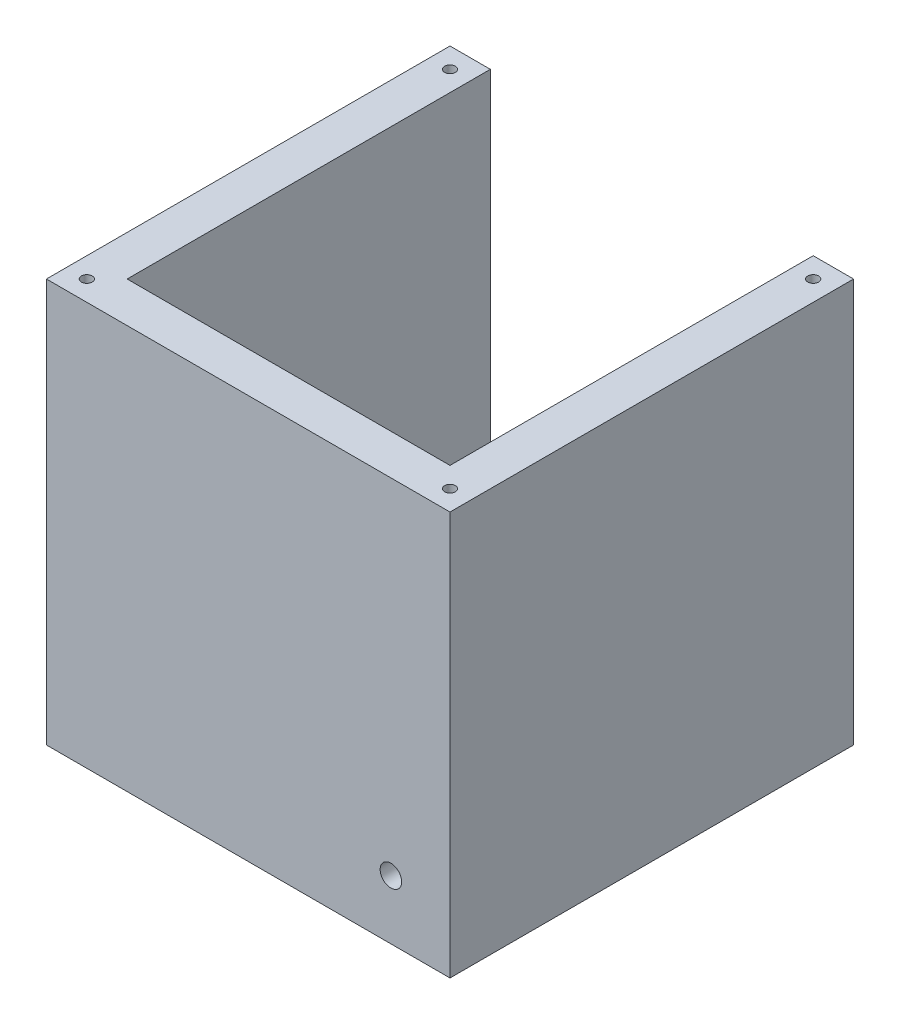
SolidWorks part; units mm, degrees
ref_plane "Alzado" through (0, 0, 0) normal (0, 0, 1) x (1, 0, 0)
ref_plane "Planta" through (0, 0, 0) normal (0, 1, 0) x (1, 0, 0)
ref_plane "Vista lateral" through (0, 0, 0) normal (1, 0, 0) x (0, 0, -1)
sketch "Croquis1" plane through (0, 0, 0) normal (0, 0, 1) x (1, 0, 0)
  line L1 (-75, -75) -> (75, -75)
  line L2 (-75, -75) -> (-75, 75)
  line L3 (-75, 75) -> (75, 75)
  line L4 (75, -75) -> (75, 75)
  line L5 (-75, -75) -> (75, 75) construction
  line L6 (-75, 75) -> (75, -75) construction
  point P0 (0, 0)
extrude "Saliente-Extruir1" add sketch "Croquis1" along normal blind 150
sketch "Croquis2" plane through (0, 0, 0) normal (0, 0, -1) x (-1, 0, 0)
  line L0 (60, 60) -> (60, -60)
  line L1 (60, 60) -> (-60, 60)
  line L2 (60, -60) -> (-60, -60)
  line L3 (-60, 60) -> (-60, -60)
  line L4 (60, 60) -> (-60, -60) construction
  line L5 (60, -60) -> (-60, 60) construction
  line L6 (-60, 60) -> (-60, 75)
  line L7 (-75, 75) -> (75, 75) construction
  line L8 (-60, 75) -> (60, 75)
  line L9 (60, 75) -> (60, 60)
  point P1 (0, 0)
  line M4 (75, 75) -> (-75, 75)
extrude "Cortar-Extruir1" cut sketch "Croquis2" against normal blind 135 contours L9 L6 L1 M4 | L1 L3 L2 L0
sketch "Croquis3" plane through (0, 75, 0) normal (0, 1, 0) x (1, 0, 0)
  line L0 (-60, -135) -> (-75, -150)
  circle A0 centre (-67.5, -142.5) radius 2
  circle A1 centre (67.5, -142.5) radius 2
  circle A2 centre (67.5, -7.5) radius 2
  circle A3 centre (-67.5, -7.5) radius 2
  dimension "D1" = 2
  dimension "D2" = 2
extrude "Cortar-Extruir2" cut sketch "Croquis3" against normal blind 10 contours A0 | A1 | A2 | A3
sketch "Croquis4" plane through (0, 0, 0) normal (0, 0, -1) x (-1, 0, 0)
  line L0 (-60, -60) -> (-75, -75)
  circle A0 centre (-67.5, -67.5) radius 2
  circle A1 centre (67.5, -67.5) radius 2
  circle A2 centre (67.5, 67.5) radius 2
  circle A3 centre (-67.5, 67.5) radius 2
  dimension "D1" = 2
  dimension "D2" = 2
extrude "Cortar-Extruir3" cut sketch "Croquis4" against normal blind 10 contours A0 | A1 | A2 | A3
sketch "Croquis5" plane through (0, 0, 150) normal (0, 0, 1) x (1, 0, 0)
  line L0 (0, 0) -> (75, -75)
  circle A0 centre (53.033, -53.033) radius 4
  dimension "D1" = 8
  dimension "D2" = 75
extrude "Cortar-Extruir4" cut sketch "Croquis5" against normal blind 15 contours A0
